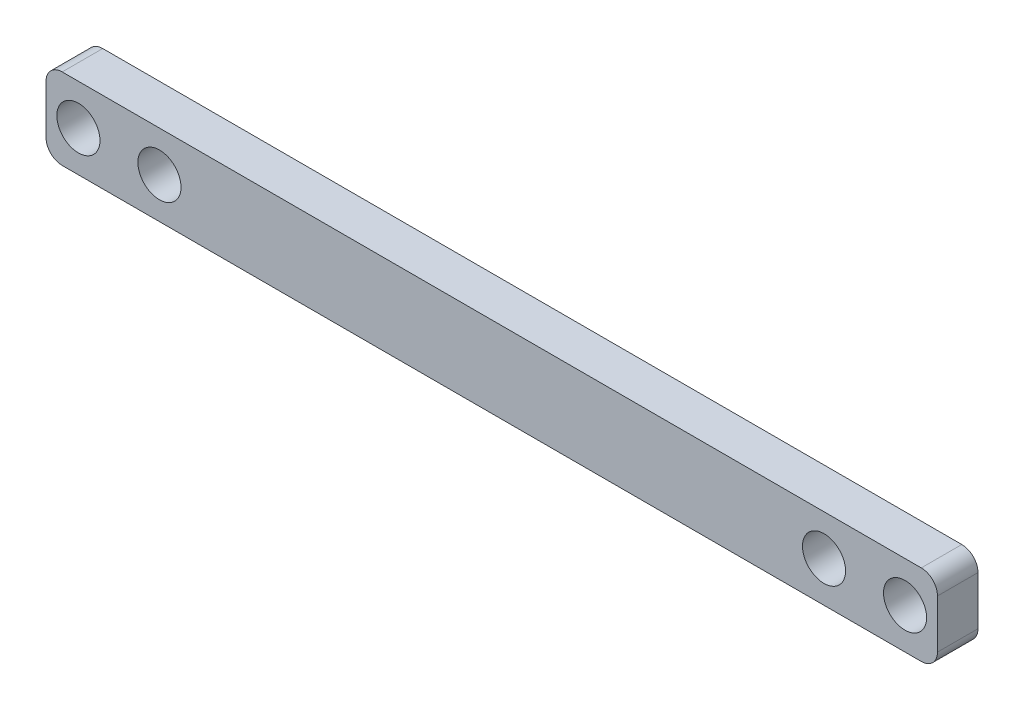
SolidWorks part; units mm, degrees
material "6061-T6 (SS)"
ref_plane "Front Plane" through (0, 0, 0) normal (0, 0, 1) x (1, 0, 0)
ref_plane "Top Plane" through (0, 0, 0) normal (0, 1, 0) x (1, 0, 0)
ref_plane "Right Plane" through (0, 0, 0) normal (1, 0, 0) x (0, 0, -1)
sketch "Sketch1" plane through (0, 0, 0) normal (0, 0, 1) x (1, 0, 0)
  line L1 (-69.85, -6.35) -> (69.85, -6.35)
  line L2 (-69.85, -6.35) -> (-69.85, 6.35)
  line L3 (-69.85, 6.35) -> (69.85, 6.35)
  line L4 (69.85, -6.35) -> (69.85, 6.35)
  line L5 (-69.85, -6.35) -> (69.85, 6.35) construction
  line L6 (-69.85, 6.35) -> (69.85, -6.35) construction
  point P0 (0, 0)
  dimension "D1" = 139.7
  dimension "D2" = 12.7
extrude "Boss-Extrude1" add sketch "Sketch1" along normal blind 6.35
hole_wizard "H (0.266) Diameter Hole1" positions "Sketch3" profile "Sketch2" hole size "H" standard "Ansi Inch" end condition through all
sketch "Sketch3" plane through (0, 0, 6.35) normal (0, 0, 1) x (1, 0, 0)
  line L1 (-52.07, 0) -> (52.07, 0) construction
  line L4 (-64.77, 0) -> (64.77, 0) construction
  point P0 (-64.77, 0)
  point P1 (-52.07, 0)
  point P3 (52.07, 0)
  point P5 (64.77, 0)
  dimension "D2" = 104.14
  dimension "D3" = 129.54
sketch "Sketch2" plane through (-64.77, 0, 6.35) normal (1, 0, 0) x (0, -1, 0)
  line L0 (0, 0) -> (0, 6.35)
  line L1 (0, 6.35) -> (3.3782, 6.35)
  line L2 (3.3782, 6.35) -> (3.3782, 0)
  line L5 (3.3782, 0) -> (0, 0)
  line L11 (0, -6.35) -> (0, 107.95) construction
  dimension "Thru Hole Dia." = 6.7564
  dimension "Thru Hole Depth" = 6.35
fillet "Fillet1" radius 2.54 4 edges at (69.85, 6.35, 3.175) (69.85, -6.35, 3.175) (-69.85, -6.35, 3.175) (-69.85, 6.35, 3.175)
